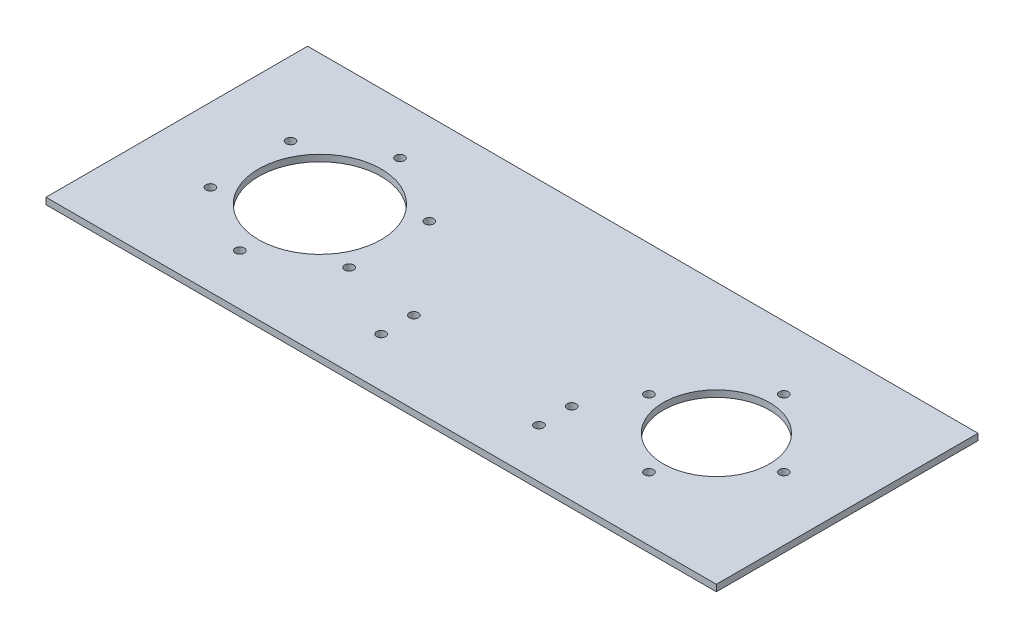
SolidWorks part; units mm, degrees
ref_plane "Front Plane" through (0, 0, 0) normal (0, 0, 1) x (1, 0, 0)
ref_plane "Top Plane" through (0, 0, 0) normal (0, 1, 0) x (1, 0, 0)
ref_plane "Right Plane" through (0, 0, 0) normal (1, 0, 0) x (0, 0, -1)
sketch "Sketch1" plane through (0, 0, 0) normal (0, 1, 0) x (1, 0, 0)
  line L1 (-175, -160) -> (645, -160)
  line L2 (-175, -160) -> (-175, 160)
  line L3 (-175, 160) -> (645, 160)
  line L4 (645, -160) -> (645, 160)
  circle A0 centre (0, 0) radius 75
  circle A1 centre (0, 0) radius 98 construction
  circle A2 centre (0, -98) radius 5.5
  circle A3 centre (-84.8705, -49) radius 5.5
  circle A4 centre (-84.8705, 49) radius 5.5
  circle A5 centre (0, 98) radius 5.5
  circle A6 centre (84.8705, 49) radius 5.5
  circle A7 centre (84.8705, -49) radius 5.5
  circle A8 centre (485, 0) radius 65
  circle A9 centre (485, 0) radius 82.5 construction
  circle A10 centre (567.5, 0) radius 5.5
  circle A14 centre (485, -82.5) radius 5.5
  circle A15 centre (402.5, 0) radius 5.5
  circle A16 centre (485, 82.5) radius 5.5
  point P4 (-175, 0)
  point P23 (0, 0)
  point P36 (250, 0)
  point P37 (485, 0)
  dimension "D2" = 150
  dimension "D3" = 196
  dimension "D4" = 11
  dimension "D8" = 130
  dimension "D9" = 165
  dimension "D10" = 11
  dimension "D1" = 320
  dimension "D6" = 175
  dimension "D7" = 485
  dimension "D12" = 820
  dimension "D5" = 6
  dimension "D11" = 4
extrude "Boss-Extrude1" add sketch "Sketch1" along normal blind 8 contours L1 L4 L3 L2 A10 A8 A7 A6 A5 A4 A3 A2 A0
sketch "Sketch2" plane through (0, 0, 0) normal (0, 1, 0) x (1, 0, 0)
  line L0 (235, 160) -> (235, -160) construction
  line L1 (-175, 160) -> (645, 160) construction
  line L2 (-175, -160) -> (645, -160) construction
  line L3 (175, -60) -> (368, -60) construction
  line L4 (368, -60) -> (368, -100) construction
  line L5 (368, -100) -> (175, -100) construction
  line L6 (175, -100) -> (175, -60) construction
  circle A0 centre (175, -60) radius 5.5
  circle A1 centre (175, -100) radius 5.5
  circle A2 centre (368, -100) radius 5.5
  circle A3 centre (368, -60) radius 5.5
  dimension "D5" = 11
  dimension "D1" = 193
  dimension "D2" = 40
  dimension "D3" = 60
  dimension "D4" = 60
extrude "Cut-Extrude2" cut sketch "Sketch2" along normal blind 10
equation "\"d_ext_rouleau\"= 90"
equation "\"epaisseur_rouleau\"=80"
equation "\"alesage-rouleau\"= 52"
equation "\"jeu_dent_rouleau\"= 2"
equation "\"profondeur_dent_rouleau\"=4"
equation "\"n_dent_roueau\"= 15"
equation "\"d_ext_roulement_rouleau\"= 42"
equation "\"d_int_roulement_rouleau\"= 20"
equation "\"B_roulement_rouleau\"= 12"
equation "\"r_roulement_rouleau\"= 0.6"
equation "\"d_bille_roulement_rouleau\"= 8"
equation "\"F_anneau_alesage_rouleau\"=1.85"
equation "\"G_anneau_alesage_rouleau\"=47.5"
equation "\"K_anneau_alesage_rouleau\"=3.75"
equation "\"d_vis_flasque_rouleau\"=5"
equation "\"l-x_vis_flasque_rouleau\"=4"
equation "\"g_anneau_arbre_rouleau\"=19"
equation "\"f_anneau_arbre_rouleau\"=1.3"
equation "\"k_anneau_arbre_rouleau\"=1.5"
equation "\"entrax_vis_rouleau\"=65"
equation "\"d_granulat\"= 8"
equation "\"h_matrice\"= 22"
equation "\"d_matrice\"= 220"
equation "\"zone_vide_matrice\" = 48"
equation "\"d_alesage_matrice\"=20"
equation "\"a_clavette_alesage_matrice\"=6"
equation "\"B_roulement_matrice\"= 12"
equation "\"d_ext_roulement_matrice\"= 42"
equation "\"d_int_roulement_matrice\"= 20"
equation "\"r_roulement_matrice\"= 1"
equation "\"h_epaulement_arbre_matrice\" = 80"
equation "\"j_clavette_arbre_matrice\" = 6"
equation "\"g_anneaux_arbre_matrice\" = 19"
equation "\"f_anneaux_arbre_matrice\" = 1.3"
equation "\"B_roulement_bc_arbre_matrice\"= 10"
equation "\"e_anneaux_arbre_matrice\" = 1.2"
equation "\"h_polie_matrice\" = 40"
equation "\"l_arbre_matrice\" = 300"
equation "\"d_int_ecrou_encouch_matrice\" = 20"
equation "\"d_ext_ecrou_encouch_matrice\" = 32"
equation "\"b_ecrou_encouch_matrice\" = 6"
equation "\"s_ecrou_encouch_matrice\" = 4"
equation "\"G_ecrou_encouch_matrice\" = 1"
equation "\"E_ecrou_encouch_matrice\" = 4"
equation "\"d_int_roulement_conique_matrice\"=25"
equation "\"d_ext_roulement_conique_matrice\"=52"
equation "\"b_roulement_conique_matrice\"=16.25"
equation "\"d_int_roulement_bc_matrice\"=20"
equation "\"d_ext_roulement_bc_matrice\"=42"
equation "\"b_roulement_bc_matrice\" = 12"
equation "\"d_tube_sup_carter\"=244.5"
equation "\"e_tube_sup_carter\"=12"
equation "\"d_tube_inf_catrer\"= 168.3"
equation "\"e_tube_inf_carter\"= 6"
equation "\"d_tube_inf_carter_cache\" = 244.5"
equation "\"e_tube_inf_carter_cache\" = 8"
equation "\"d_tube_sup_carter_cache\" = 133"
equation "\"e_tube_sup_carter_cache\" = 4"
equation "\"h_tube_trimee\" = 40"
equation "\"e_tole\" = 8"
equation "\"entraxe_vis_carter\" = 196"
equation "\"D3@Sketch1\"=\"entraxe_vis_carter\""
equation "\"d_vis_H_carter\"=10"
equation "\"entraxe_courroie\"= 485"
equation "\"D7@Sketch1\"=\"entraxe_courroie\""
equation "\"D10@Sketch1\"=11"
equation "\"d_int_polie_matrice\" = 16"
equation "\"L_base\" = 820"
equation "\"larg_base\" = 320"
equation "\"D1@Sketch1\"=\"larg_base\""
equation "\"D12@Sketch1\"=\"L_base\""
